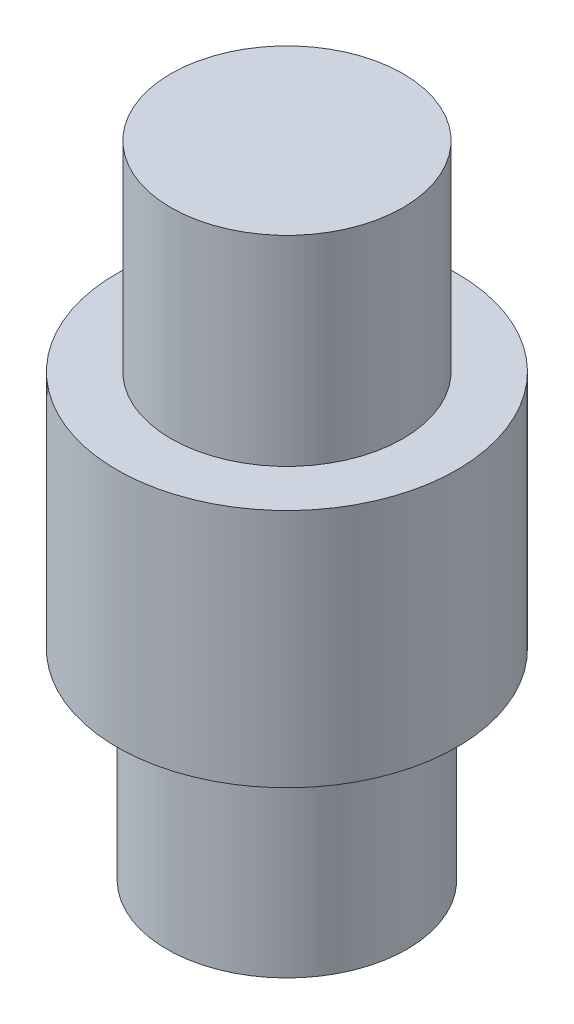
SolidWorks part; units mm, degrees
ref_plane "Front" through (0, 0, 0) normal (0, 0, 1) x (1, 0, 0)
ref_plane "Top" through (0, 0, 0) normal (0, 1, 0) x (1, 0, 0)
ref_plane "Right" through (0, 0, 0) normal (1, 0, 0) x (0, 0, -1)
sketch "Sketch1" plane through (0, 0, 0) normal (0, 1, 0) x (1, 0, 0)
  circle A0 centre (0, 0) radius 1.45
  dimension "D1" = 2.9
extrude "Boss-Extrude1" add sketch "Sketch1" along normal blind 2.5
sketch "Sketch2" plane through (0, 0, 0) normal (0, -1, 0) x (1, 0, 0)
  circle A0 centre (0, 0) radius 2.125
  dimension "D1" = 4.25
extrude "Boss-Extrude2" add sketch "Sketch2" along normal blind 3
sketch "Sketch3" plane through (0, -3, 0) normal (0, -1, 0) x (1, 0, 0)
  circle A0 centre (0, 0) radius 1.5
  dimension "D1" = 3
extrude "Boss-Extrude3" add sketch "Sketch3" along normal blind 2.5
